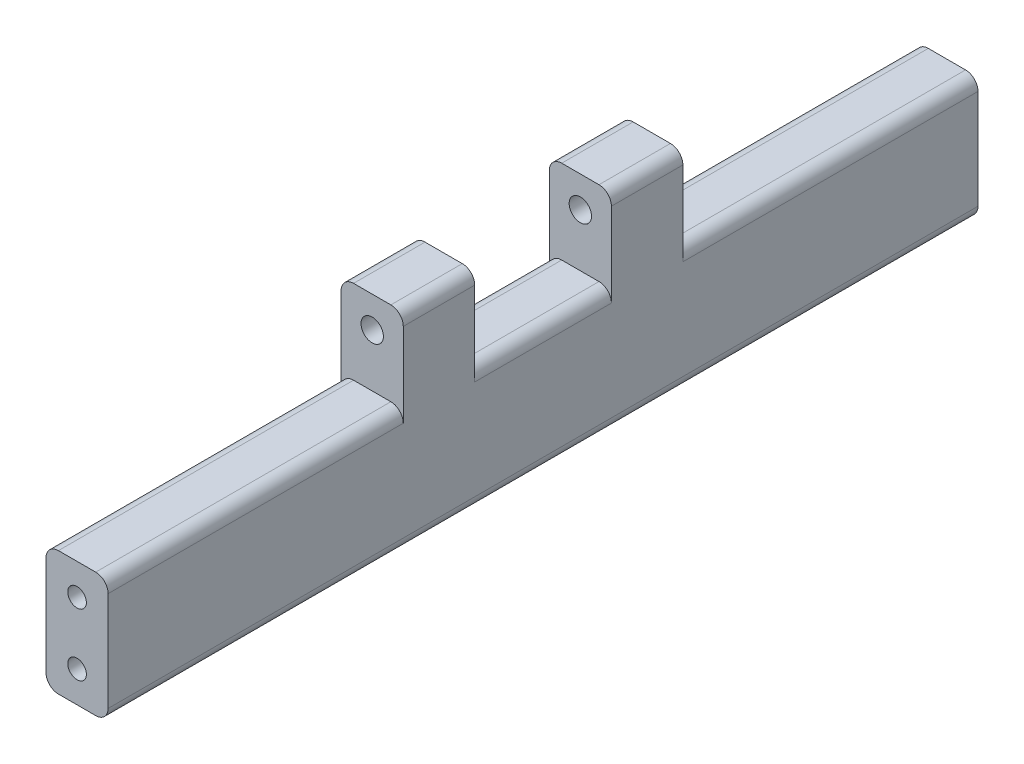
SolidWorks part; units mm, degrees
ref_plane "Front Plane" through (0, 0, 0) normal (0, 0, 1) x (1, 0, 0)
ref_plane "Top Plane" through (0, 0, 0) normal (0, 1, 0) x (1, 0, 0)
ref_plane "Right Plane" through (0, 0, 0) normal (1, 0, 0) x (0, 0, -1)
sketch "Sketch1" plane through (0, 0, 0) normal (0, 0, 1) x (1, 0, 0)
  line L0 (-12.7, 0) -> (0, 0) construction
  line L7 (-12.7, 12.7) -> (0, 12.7)
  line L8 (-12.7, 12.7) -> (-12.7, -12.7)
  line L9 (-12.7, -12.7) -> (0, -12.7)
  line L10 (0, 12.7) -> (0, -12.7)
  circle A0 centre (-6.35, 6.35) radius 1.905
  circle A2 centre (-6.35, 6.35) radius 2.286 construction
  circle A3 centre (-6.35, -6.35) radius 1.905
  point P10 (-12.7, 0)
  point P11 (0, 0)
  dimension "D4" = 3.81
  dimension "D5" = 12.7
  dimension "D6" = 25.4
extrude "Boss-Extrude1" add sketch "Sketch1" against normal mid plane 177.8 contours L0 L8 L9 L10 A3 | L8 L0 L10 L7 A0
sketch "Sketch3" plane through (0, 0, 0) normal (0, 0, 1) x (1, 0, 0)
  line L0 (-12.7, 12.7) -> (-12.7, 29.845)
  line L1 (-12.7, 29.845) -> (0, 29.845)
  line L2 (0, 29.845) -> (0, 12.7)
  line L4 (0, 12.7) -> (-12.7, 12.7)
  circle A0 centre (-6.35, 23.495) radius 2.286
  point P9 (-6.35, 12.7)
  dimension "D1" = 4.572
  dimension "D2" = 6.35
  dimension "D3" = 10.795
extrude "Boss-Extrude2" add sketch "Sketch3" along normal mid plane 57.15
sketch "Sketch4" plane through (0, 0, 0) normal (0, 0, 1) x (1, 0, 0)
  line L1 (-12.7, 29.845) -> (0, 29.845)
  line L2 (-12.7, 29.845) -> (-12.7, 12.7)
  line L3 (-12.7, 12.7) -> (0, 12.7)
  line L4 (0, 29.845) -> (0, 12.7)
extrude "Cut-Extrude1" cut sketch "Sketch4" against normal mid plane 27.94
fillet "Fillet1" radius 2.54 12 edges at (-12.7, -12.7, 0) (0, -12.7, 0) (-12.7, 29.845, -21.2725) (0, 29.845, -21.2725) (-12.7, 12.7, -58.7375) (0, 12.7, -58.7375) (-12.7, 12.7, 0) (0, 12.7, 0) (-12.7, 29.845, 21.2725) (0, 29.845, 21.2725) (-12.7, 12.7, 58.7375) (0, 12.7, 58.7375)
